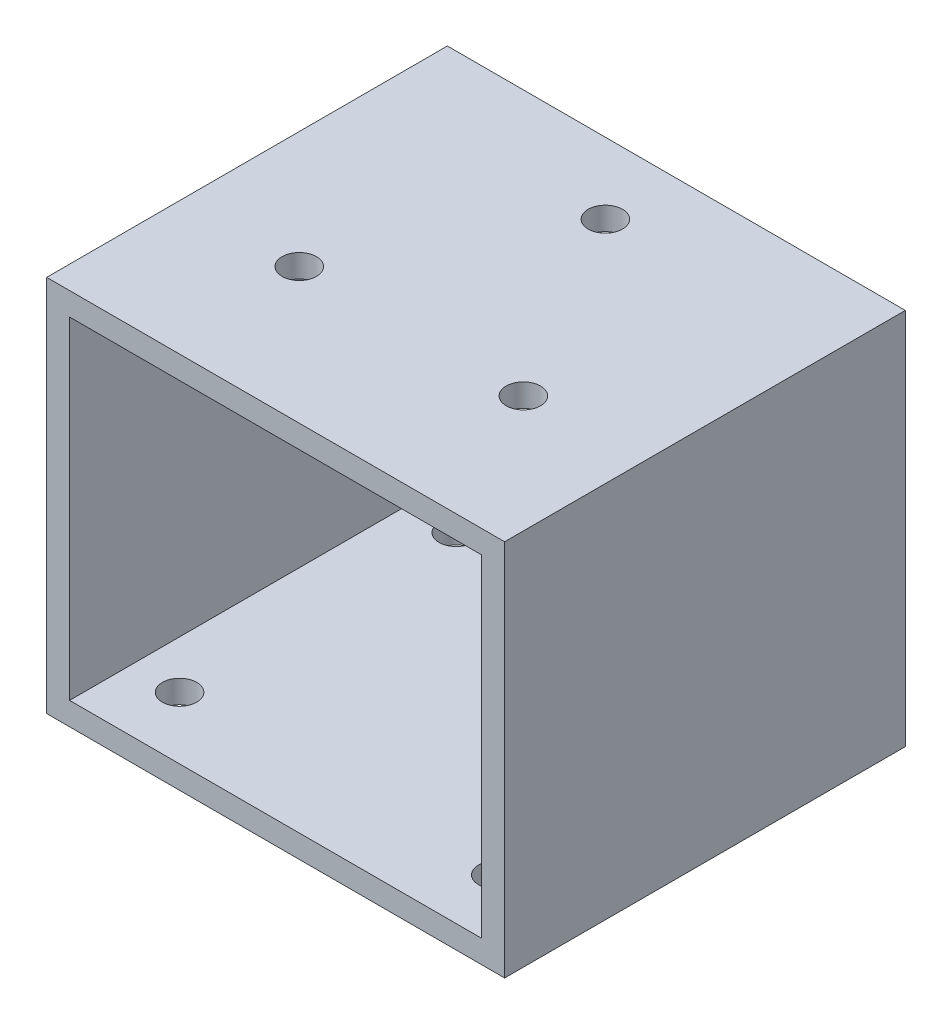
SolidWorks part; units mm, degrees
ref_plane "Front Plane" through (0, 0, 0) normal (0, 0, 1) x (1, 0, 0)
ref_plane "Top Plane" through (0, 0, 0) normal (0, 1, 0) x (1, 0, 0)
ref_plane "Right Plane" through (0, 0, 0) normal (1, 0, 0) x (0, 0, -1)
sketch "Sketch1" plane through (0, 0, 0) normal (0, 0, 1) x (1, 0, 0)
  line L0 (-20, 16.5) -> (20, 16.5)
  line L1 (-20, 16.5) -> (-20, -16.5)
  line L2 (20, 16.5) -> (20, -16.5)
  line L3 (-20, -16.5) -> (20, -16.5)
  line L4 (-18, 14.5) -> (18, 14.5)
  line L5 (18, 14.5) -> (18, -14.5)
  line L6 (-18, -14.5) -> (18, -14.5)
  line L7 (-18, 14.5) -> (-18, -14.5)
  dimension "D1" = 40
  dimension "D2" = 33
  dimension "D3" = 16.5
  dimension "D4" = 20
  dimension "D5" = 2
extrude "Boss-Extrude1" add sketch "Sketch1" along normal blind 35
sketch "Sketch2" plane through (0, 16.5, 0) normal (0, 1, 0) x (1, 0, 0)
  line L2 (20, 0) -> (-20, 0) construction
  line L3 (20, -35) -> (20, 0) construction
  circle A0 centre (0, -6.2) radius 1.5
  circle A1 centre (9.7861, -23.15) radius 1.5
  circle A2 centre (-9.7861, -23.15) radius 1.5
  point P0 (0, -17.5)
  point P14 (0, -17.5)
  dimension "D3" = 11.3
  dimension "D1" = 17.5
  dimension "D2" = 20
  dimension "D4" = 3
extrude "Cut-Extrude1" cut sketch "Sketch2" against normal blind 15
sketch "Sketch3" plane through (0, -16.5, 0) normal (0, -1, 0) x (1, 0, 0)
  line L0 (20, 35) -> (20, 0) construction
  line L1 (-20, 35) -> (20, 35) construction
  line L2 (0, 17.5) -> (20, 35) construction
  line L3 (0, 17.5) -> (-20, 0) construction
  line L4 (-20, 35) -> (20, 0) construction
  line L5 (-9.5697, 17.5) -> (9.5697, 17.5) construction
  circle A0 centre (13.8095, 29.5833) radius 1.5
  circle A1 centre (-13.8095, 29.5833) radius 1.5
  circle A2 centre (13.8095, 5.4167) radius 1.5
  circle A3 centre (-13.8095, 5.4167) radius 1.5
  point P0 (0, 17.5)
  point P17 (0, 17.5)
  point P20 (0, 17.5)
  dimension "D1" = 20
  dimension "D2" = 17.5
extrude "Cut-Extrude2" cut sketch "Sketch3" against normal blind 15
